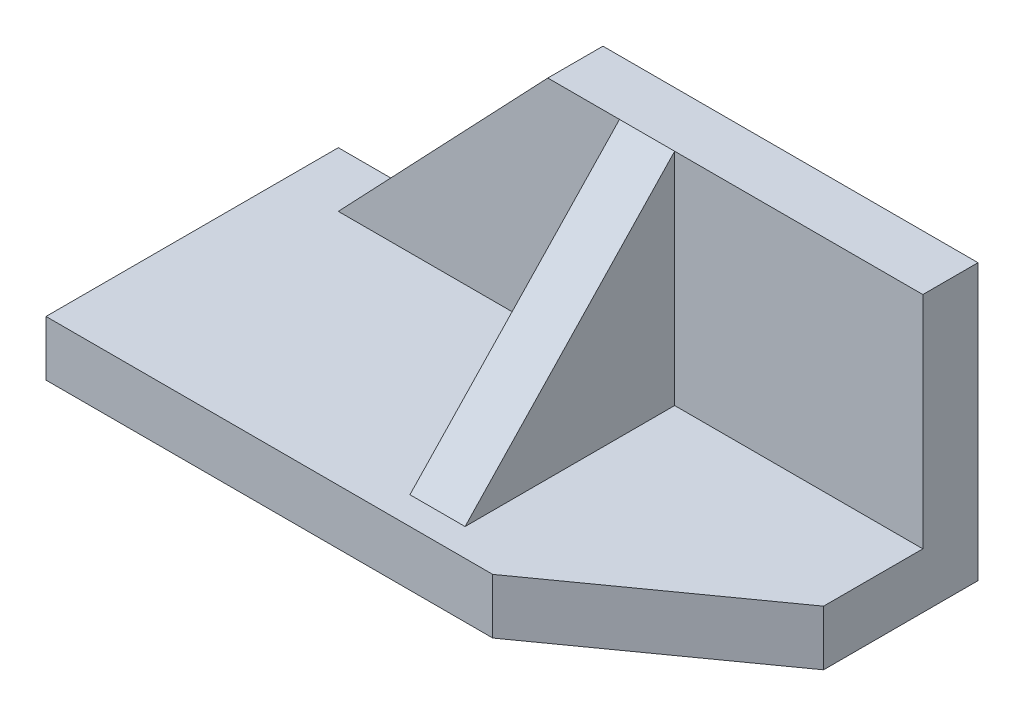
SolidWorks part; units mm, degrees
ref_plane "Front Plane" through (0, 0, 0) normal (0, 0, 1) x (1, 0, 0)
ref_plane "Top Plane" through (0, 0, 0) normal (0, 1, 0) x (1, 0, 0)
ref_plane "Right Plane" through (0, 0, 0) normal (1, 0, 0) x (0, 0, -1)
sketch "Sketch2" plane through (0, 0, 0) normal (0, 1, 0) x (1, 0, 0)
  line L0 (42.4401, 0) -> (77.4229, 25)
  line L1 (-38.5599, 0) -> (42.4401, 0)
  line L2 (-38.5599, 0) -> (-38.5599, 53)
  line L3 (-38.5599, 53) -> (42.4401, 53)
  line L4 (42.4401, 0) -> (42.4401, 53)
  line L5 (77.4229, 25) -> (77.4229, 53)
  line L6 (77.4229, 53) -> (42.4401, 53)
  dimension "D1" = 81
  dimension "D2" = 53
  dimension "D3" = 25
extrude "Boss-Extrude1" add sketch "Sketch2" against normal blind 10 contours L5 L6 L4 L0 | L1 L4 L3 L2
sketch "Sketch3" plane through (0, 0, -53) normal (0, 0, -1) x (-1, 0, 0)
  line L0 (-77.4229, 0) -> (-77.4229, 39.9323)
  line L1 (-77.4229, 39.9323) -> (-9.4229, 39.9323)
  line L2 (-9.4229, 39.9323) -> (28.5599, 0)
  line L3 (-77.4229, 0) -> (38.5599, 0) construction
  line L4 (28.5599, 0) -> (-77.4229, 0)
  dimension "D1" = 68
  dimension "D2" = 10
extrude "Boss-Extrude2" add sketch "Sketch3" against normal blind 10
ref_plane "Plane1" through (32.4229, 0, 0) normal (1, 0, 0) x (0, 0, -1)
sketch "Sketch4" plane through (32.4229, 0, 0) normal (1, 0, 0) x (0, 0, -1)
  line L0 (43, 39.9323) -> (5, 0)
  line L1 (0, 0) -> (25, 0) construction
  line L2 (5, 0) -> (43, 0)
  line L3 (43, 0) -> (43, 39.9323)
  dimension "D1" = 38
extrude "Boss-Extrude3" add sketch "Sketch4" against normal blind 10
